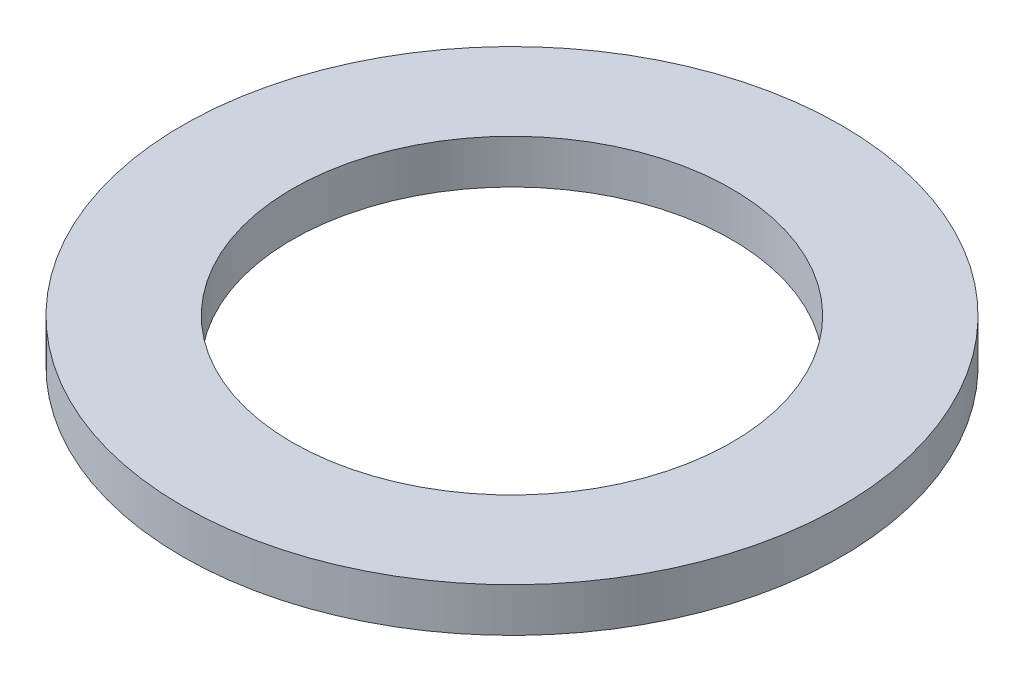
SolidWorks part; units mm, degrees
ref_plane "Front Plane" through (0, 0, 0) normal (0, 0, 1) x (1, 0, 0)
ref_plane "Top Plane" through (0, 0, 0) normal (0, 1, 0) x (1, 0, 0)
ref_plane "Right Plane" through (0, 0, 0) normal (1, 0, 0) x (0, 0, -1)
sketch "Sketch1" plane through (0, 0, 0) normal (0, 1, 0) x (1, 0, 0)
  circle A0 centre (0, 0) radius 4.7625
  dimension "OD" = 9.525
extrude "Boss-Extrude1" add sketch "Sketch1" along normal blind 0.635
sketch "Sketch5" plane through (0, 0.635, 0) normal (0, 1, 0) x (-1, 0, 0)
  circle A0 centre (0, 0) radius 3.175
  dimension "ID" = 6.35
extrude "Cut-Extrude1" cut sketch "Sketch5" against normal through all
